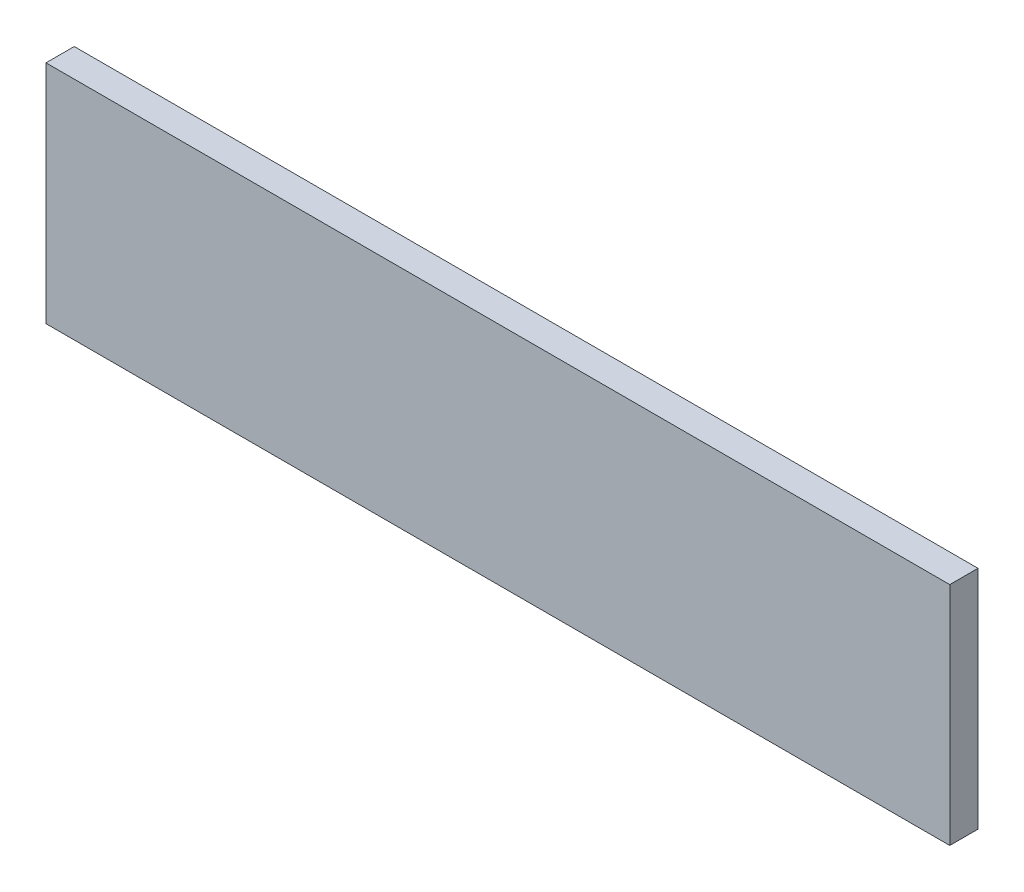
SolidWorks part; units mm, degrees
ref_plane "Front Plane" through (0, 0, 0) normal (0, 0, 1) x (1, 0, 0)
ref_plane "Top Plane" through (0, 0, 0) normal (0, 1, 0) x (1, 0, 0)
ref_plane "Right Plane" through (0, 0, 0) normal (1, 0, 0) x (0, 0, -1)
sketch "Sketch1" plane through (0, 0, 0) normal (0, 0, 1) x (1, 0, 0)
  line L1 (-50.8, -12.7) -> (50.8, -12.7)
  line L2 (-50.8, -12.7) -> (-50.8, 12.7)
  line L3 (-50.8, 12.7) -> (50.8, 12.7)
  line L4 (50.8, -12.7) -> (50.8, 12.7)
  line L5 (-50.8, -12.7) -> (50.8, 12.7) construction
  line L6 (-50.8, 12.7) -> (50.8, -12.7) construction
  point P0 (0, 0)
  dimension "D1" = 101.6
  dimension "D2" = 25.4
extrude "Boss-Extrude1" add sketch "Sketch1" along normal mid plane 3.175
